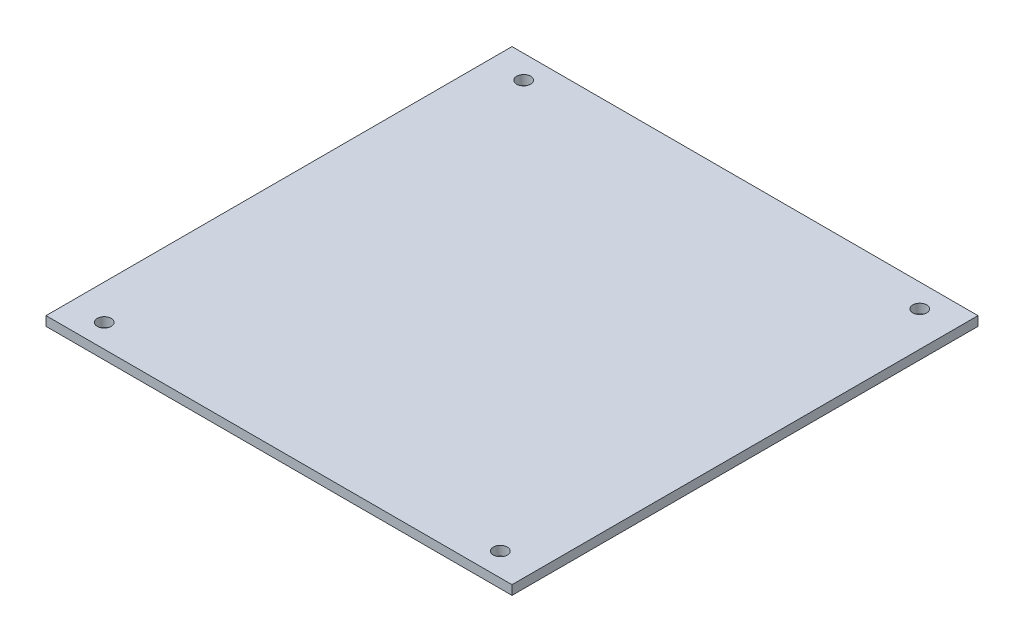
SolidWorks part; units mm, degrees
ref_plane "前视基准面" through (0, 0, 0) normal (0, 0, 1) x (1, 0, 0)
ref_plane "上视基准面" through (0, 0, 0) normal (0, 1, 0) x (1, 0, 0)
ref_plane "右视基准面" through (0, 0, 0) normal (1, 0, 0) x (0, 0, -1)
sketch "Sketch1" plane through (0, 0, 0) normal (0, 1, 0) x (1, 0, 0)
  line L1 (-50, 50) -> (50, 50)
  line L2 (-50, 50) -> (-50, -50)
  line L3 (-50, -50) -> (50, -50)
  line L4 (50, 50) -> (50, -50)
  line L5 (-50, 50) -> (50, -50) construction
  line L6 (-50, -50) -> (50, 50) construction
  point P0 (0, 0)
extrude "Extrude1" add sketch "Sketch1" along normal blind 2
sketch "Sketch3" plane through (0, 2, 0) normal (0, 1, 0) x (1, 0, 0)
  circle A0 centre (-42.5, 45) radius 1.5
  circle A1 centre (-42.5, -45) radius 1.5
  circle A2 centre (42.5, -45) radius 1.5
  circle A3 centre (42.5, 45) radius 1.5
extrude "Extrude2" cut sketch "Sketch3" against normal blind 2
